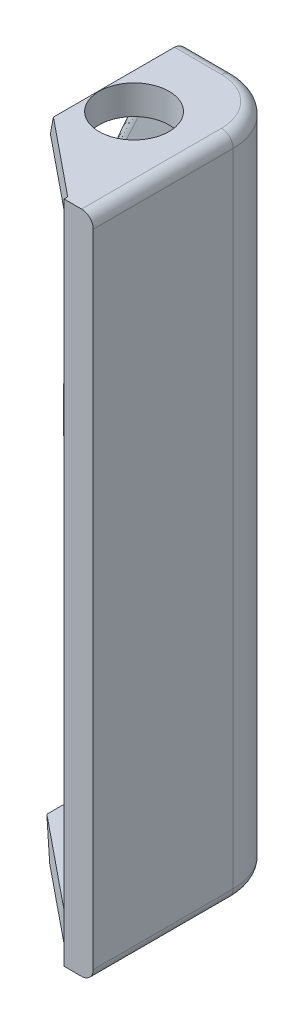
SolidWorks part; units mm, degrees
material "Silicon Rubber"
ref_plane "Front Plane" through (0, 0, 0) normal (0, 0, 1) x (1, 0, 0)
ref_plane "Top Plane" through (0, 0, 0) normal (0, 1, 0) x (1, 0, 0)
ref_plane "Right Plane" through (0, 0, 0) normal (1, 0, 0) x (0, 0, -1)
sketch "Sketch2" plane through (0, 0, 0) normal (0, 1, 0) x (1, 0, 0)
  line L0 (0, 0) -> (101.6, 0)
  line L1 (0, 0) -> (0, -12.7)
  line L2 (0, -12.7) -> (88.9, -12.7)
  line L3 (127, -25.4) -> (127, -86.36)
  line L4 (114.3, -38.1) -> (114.3, -86.36)
  line L5 (114.3, -86.36) -> (127, -86.36)
  arc A0 (127, -25.4) -> (101.6, 0) centre (101.6, -25.4) ccw
  arc A1 (88.9, -12.7) -> (114.3, -38.1) centre (88.9, -38.1) cw
  dimension "D5" = 25.4
  dimension "D1" = 12.7
  dimension "D2" = 86.36
  dimension "D3" = 127
  dimension "D4" = 12.7
extrude "Boss-Extrude1" add sketch "Sketch2" along normal mid plane 289.56
sketch "Sketch3" plane through (0, 144.78, 0) normal (0, 1, 0) x (1, 0, 0)
  line L0 (25.5919, -12.7) -> (114.3, -84.7789)
  line L1 (0, -12.7) -> (88.9, -12.7) construction
  line L2 (114.3, -38.1) -> (114.3, -86.36) construction
  dimension "D1" = 114.3
rib "Rib1" sketch "Sketch3" sketch "Sketch3" thickness 12.7 extrusion direction parallel to sketch draft on no parameters "D1"=12.7
mirror "Mirror1" about plane through (0, 0, 0) normal (0, 1, 0) of "Rib1"
sketch "Sketch4" plane through (0, 0, 0) normal (0, 0, -1) x (-1, 0, 0)
  line L2 (-81.0897, 144.78) -> (0, 144.78)
  line L3 (-72.4539, -144.78) -> (0, -144.78)
  line L4 (0, 144.78) -> (0, -144.78)
  line L5 (-101.6, -144.78) -> (0, -144.78) construction
  spline S0 degree 3 poles (-81.0897, 144.78) (-22.4966, 42.3154) (-25.9236, -60.2162) (-72.4539, -144.78) knots 0 0 0 0 1 1 1 1
extrude "Cut-Extrude1" cut sketch "Sketch4" against normal blind 289.56
fillet "Fillet1" radius 5.08 8 edges at (127, -144.78, 55.88) (119.5605, -144.78, 7.4395) (127, 144.78, 55.88) (119.5605, 144.78, 7.4395) (87.0269, -144.78, 0) (91.3448, 144.78, 0)
sketch "Sketch5" plane through (0, -144.78, 0) normal (0, -1, 0) x (1, 0, 0)
  line L0 (127, 86.36) -> (127, 25.4) construction
  line L1 (101.6, 0) -> (75.4742, 0) construction
  circle A0 centre (96.52, 38.1) radius 15.24
  dimension "D1" = 30.48
  dimension "1" = 30.48
  dimension "D2" = 38.1
extrude "Cut-Extrude2" cut sketch "Sketch5" against normal through all
